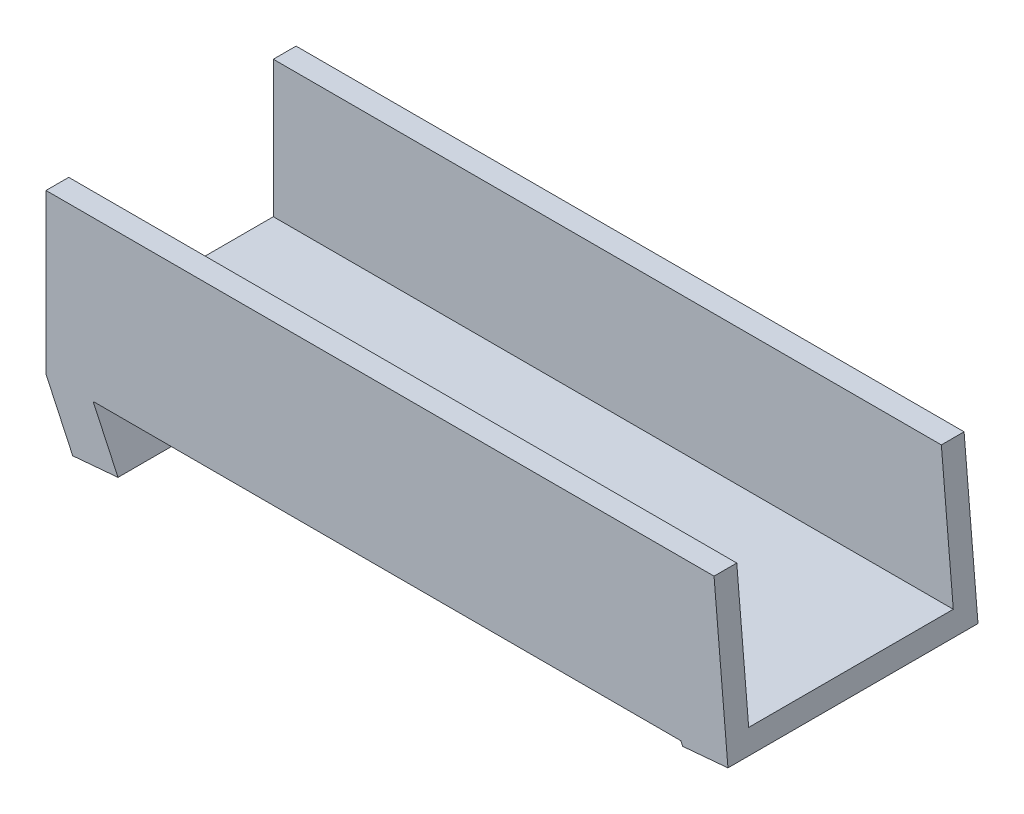
SolidWorks part; units mm, degrees
ref_plane "Plan de face" through (0, 0, 0) normal (0, 0, 1) x (1, 0, 0)
ref_plane "Plan de dessus" through (0, 0, 0) normal (0, 1, 0) x (1, 0, 0)
ref_plane "Plan de droite" through (0, 0, 0) normal (1, 0, 0) x (0, 0, -1)
sketch "Esquisse2" plane through (0, 0, 0) normal (0, 1, 0) x (1, 0, 0)
  line L1 (0, 0) -> (150, 0)
  line L2 (0, 0) -> (0, 55)
  line L3 (0, 55) -> (150, 55)
  line L4 (150, 0) -> (150, 55)
  dimension "D1" = 150
  dimension "D2" = 55
extrude "Boss.-Extru.1" add sketch "Esquisse2" along normal blind 5
sketch "Esquisse3" plane through (0, 5, 0) normal (0, 1, 0) x (1, 0, 0)
  line L0 (0, 27.5) -> (150, 27.5) construction
  line L1 (0, 55) -> (0, 0) construction
  line L2 (150, 0) -> (150, 55) construction
  line L3 (150, 0) -> (150, 5)
  line L4 (0, 55) -> (150, 55)
  line L5 (0, 55) -> (0, 50)
  line L6 (0, 50) -> (150, 50)
  line L7 (150, 55) -> (150, 50)
  line L8 (0, 5) -> (150, 5)
  line L9 (0, 0) -> (0, 5)
  line L10 (0, 0) -> (150, 0)
  dimension "D1" = 5
extrude "Boss.-Extru.2" add sketch "Esquisse3" along normal blind 30
sketch "Esquisse4" plane through (0, 0, 0) normal (0, 0, 1) x (1, 0, 0)
  line L0 (0, 0) -> (5.8796, -12.6089)
  line L1 (5.8796, -12.6089) -> (15.8416, -11.7373)
  line L2 (15.8416, -11.7373) -> (10.3684, 0)
  line L3 (0, 0) -> (150, 0) construction
  line L4 (10.3684, 0) -> (0, 0)
  line L6 (150, 0) -> (140.0381, -0.8716)
  line L7 (140.0381, -0.8716) -> (139.6316, 0)
  line L8 (139.6316, 0) -> (150, 0)
  point P2 (0, 0)
  dimension "D1" = 110
  dimension "D2" = 110
  dimension "D3" = 10
  dimension "D4" = 10
  dimension "D6" = 65
extrude "Boss.-Extru.3" add sketch "Esquisse4" against normal up to surface (55 mm away) up to face at (75, 17.5, -55)
sketch "Esquisse5" plane through (0, 0, 0) normal (0, 0, 1) x (1, 0, 0)
  line L0 (150, 0) -> (146.9379, 35)
  line L1 (0, 35) -> (150, 35) construction
  line L2 (150, 35) -> (150, 0) construction
  line L3 (146.9379, 35) -> (150, 35)
  line L4 (150, 35) -> (150, 0)
  dimension "D1" = 5
extrude "Enlèv. mat.-Extru.1" cut sketch "Esquisse5" against normal through all
